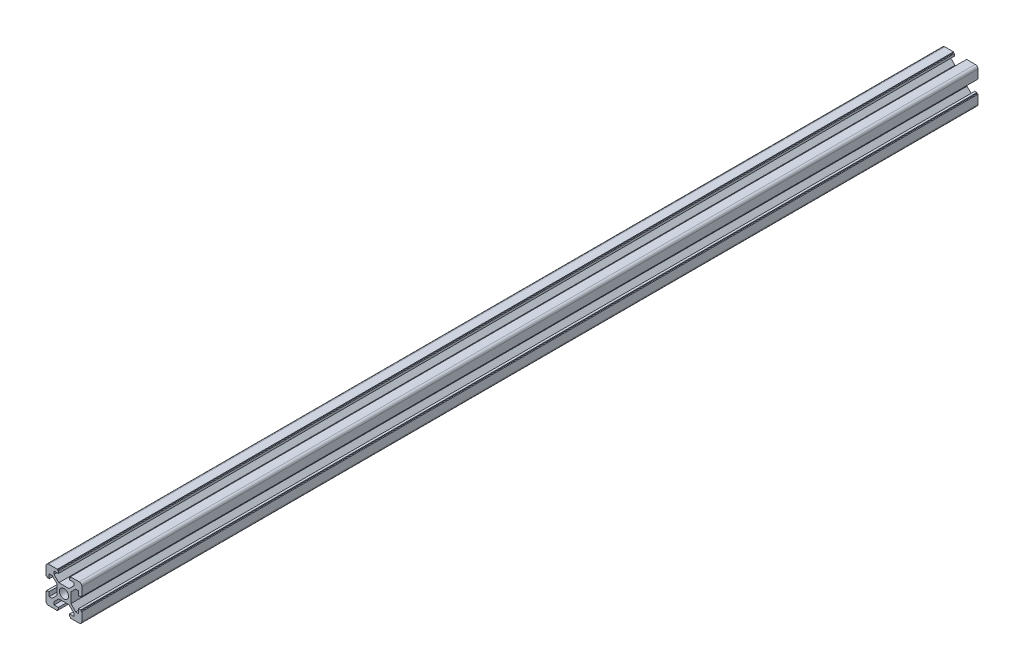
SolidWorks part; units mm, degrees
material "1060 Alloy"
ref_plane "Front Plane" through (0, 0, 0) normal (0, 0, 1) x (1, 0, 0)
ref_plane "Top Plane" through (0, 0, 0) normal (0, 1, 0) x (1, 0, 0)
ref_plane "Right Plane" through (0, 0, 0) normal (1, 0, 0) x (0, 0, -1)
sketch "Sketch2" plane through (0, 0, 0) normal (0, 0, 1) x (1, 0, 0)
  line L0 (-10, 10) -> (-3.65, 10)
  line L7 (-3.65, 10) -> (-3.65, 9.45)
  line L8 (-3.65, 9.45) -> (-3.1, 9.45)
  line L9 (-3.1, 9.45) -> (-3.1, 8.2)
  line L10 (-3.1, 8.2) -> (-5.5, 8.2)
  line L11 (-5.5, 8.2) -> (-5.5, 6.5607)
  line L18 (0, 0) -> (-10, 10) construction
  line L20 (-2.8393, 3.9) -> (-5.5, 6.5607)
  line L21 (-2.8393, 3.9) -> (0, 3.9)
  line L22 (-3.9, 2.8393) -> (-3.9, 0)
  line L23 (-3.9, 2.8393) -> (-6.5607, 5.5)
  line L24 (-8.2, 5.5) -> (-6.5607, 5.5)
  line L25 (-8.2, 3.1) -> (-8.2, 5.5)
  line L26 (-9.45, 3.1) -> (-8.2, 3.1)
  line L27 (-9.45, 3.65) -> (-9.45, 3.1)
  line L28 (-10, 3.65) -> (-9.45, 3.65)
  line L29 (-10, 10) -> (-10, 3.65)
  line L30 (2.8393, 3.9) -> (0, 3.9)
  line L31 (2.8393, 3.9) -> (5.5, 6.5607)
  line L32 (5.5, 8.2) -> (5.5, 6.5607)
  line L33 (3.1, 8.2) -> (5.5, 8.2)
  line L34 (3.1, 9.45) -> (3.1, 8.2)
  line L35 (3.65, 9.45) -> (3.1, 9.45)
  line L36 (10, 10) -> (3.65, 10)
  line L37 (10, 10) -> (10, 3.65)
  line L38 (10, 3.65) -> (9.45, 3.65)
  line L39 (9.45, 3.65) -> (9.45, 3.1)
  line L40 (9.45, 3.1) -> (8.2, 3.1)
  line L41 (8.2, 3.1) -> (8.2, 5.5)
  line L42 (8.2, 5.5) -> (6.5607, 5.5)
  line L43 (3.9, 2.8393) -> (6.5607, 5.5)
  line L44 (3.9, 2.8393) -> (3.9, 0)
  line L45 (3.65, 10) -> (3.65, 9.45)
  line L46 (3.9, -2.8393) -> (3.9, 0)
  line L47 (3.9, -2.8393) -> (6.5607, -5.5)
  line L48 (8.2, -5.5) -> (6.5607, -5.5)
  line L49 (8.2, -3.1) -> (8.2, -5.5)
  line L50 (9.45, -3.1) -> (8.2, -3.1)
  line L51 (9.45, -3.65) -> (9.45, -3.1)
  line L52 (10, -10) -> (10, -3.65)
  line L53 (10, -10) -> (3.65, -10)
  line L54 (3.65, -10) -> (3.65, -9.45)
  line L55 (3.65, -9.45) -> (3.1, -9.45)
  line L56 (3.1, -9.45) -> (3.1, -8.2)
  line L57 (3.1, -8.2) -> (5.5, -8.2)
  line L58 (5.5, -8.2) -> (5.5, -6.5607)
  line L59 (2.8393, -3.9) -> (5.5, -6.5607)
  line L60 (2.8393, -3.9) -> (0, -3.9)
  line L61 (10, -3.65) -> (9.45, -3.65)
  line L62 (-2.8393, -3.9) -> (0, -3.9)
  line L63 (-2.8393, -3.9) -> (-5.5, -6.5607)
  line L64 (-5.5, -8.2) -> (-5.5, -6.5607)
  line L65 (-3.1, -8.2) -> (-5.5, -8.2)
  line L66 (-3.1, -9.45) -> (-3.1, -8.2)
  line L67 (-3.65, -9.45) -> (-3.1, -9.45)
  line L68 (-10, -10) -> (-3.65, -10)
  line L69 (-10, -10) -> (-10, -3.65)
  line L70 (-10, -3.65) -> (-9.45, -3.65)
  line L71 (-9.45, -3.65) -> (-9.45, -3.1)
  line L72 (-9.45, -3.1) -> (-8.2, -3.1)
  line L73 (-8.2, -3.1) -> (-8.2, -5.5)
  line L74 (-8.2, -5.5) -> (-6.5607, -5.5)
  line L75 (-3.9, -2.8393) -> (-6.5607, -5.5)
  line L76 (-3.9, -2.8393) -> (-3.9, 0)
  line L77 (-3.65, -10) -> (-3.65, -9.45)
  dimension "D1" = 10
  dimension "D2" = 5.5
  dimension "D3" = 1.8
  dimension "D4" = 6.1
  dimension "D5" = 0.55
  dimension "D6" = 0.55
  dimension "D7" = 2.4
  dimension "D8" = 135
  dimension "D9" = 4
  dimension "D10" = 0.75
extrude "Boss-Extrude1" add sketch "Sketch2" against normal blind 500
sketch "Sketch3" plane through (0, 0, 0) normal (0, 0, 1) x (1, 0, 0)
  circle A0 centre (0, 0) radius 2.55
extrude "Cut-Extrude1" cut sketch "Sketch3" against normal through all contours A0
fillet "Fillet1" radius 1.5 4 edges at (-10, -10, -250) (10, -10, -250) (-10, 10, -250) (10, 10, -250)
